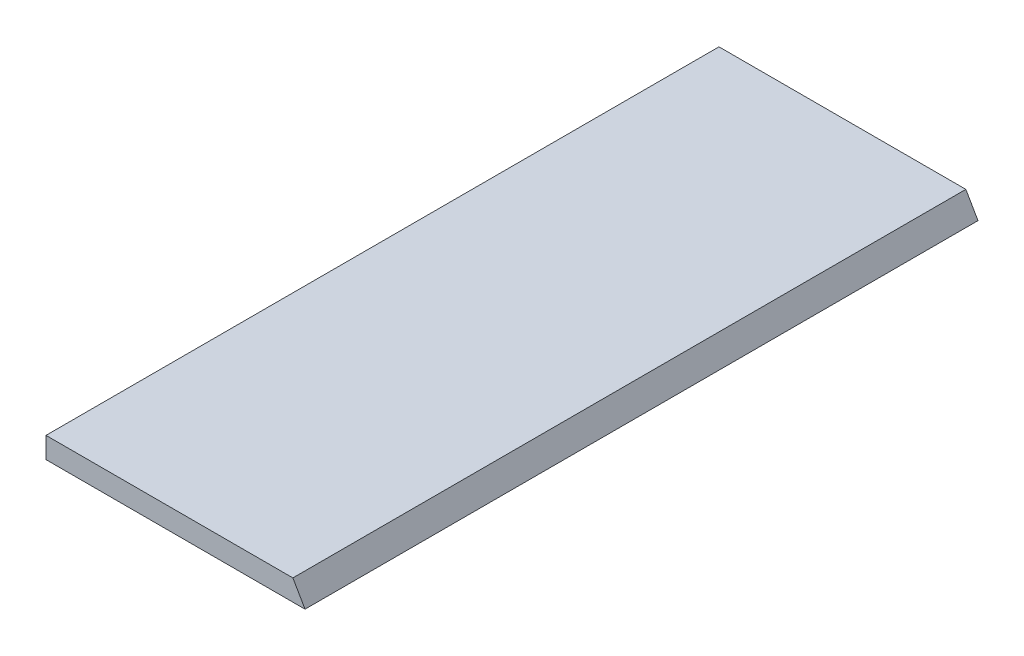
SolidWorks part; units mm, degrees
material "Oak"
ref_plane "Front Plane" through (0, 0, 0) normal (0, 0, 1) x (1, 0, 0)
ref_plane "Top Plane" through (0, 0, 0) normal (0, 1, 0) x (1, 0, 0)
ref_plane "Right Plane" through (0, 0, 0) normal (1, 0, 0) x (0, 0, -1)
sketch "Sketch1" plane through (0, 0, 0) normal (0, 1, 0) x (1, 0, 0)
  line L1 (-117.3176, -304.8) -> (117.3176, -304.8)
  line L2 (-117.3176, -304.8) -> (-117.3176, 304.8)
  line L3 (-117.3176, 304.8) -> (117.3176, 304.8)
  line L4 (117.3176, -304.8) -> (117.3176, 304.8)
  line L5 (-117.3176, -304.8) -> (117.3176, 304.8) construction
  line L6 (-117.3176, 304.8) -> (117.3176, -304.8) construction
  line L7 (234.6351, 508) -> (117.3176, 711.2) construction
  line L8 (117.3176, 711.2) -> (-117.3176, 711.2) construction
  line L9 (-117.3176, 711.2) -> (-234.6351, 508) construction
  line L10 (-234.6351, 508) -> (-117.3176, 304.8) construction
  line L11 (-117.3176, 304.8) -> (117.3176, 304.8) construction
  line L12 (117.3176, 304.8) -> (234.6351, 508) construction
  circle A0 centre (0, 508) radius 203.2 construction
  point P0 (0, 0)
  dimension "D1" = 609.6
  dimension "D2" = 406.4
extrude "Boss-Extrude1" add sketch "Sketch1" along normal blind 19.05
sketch "Sketch2" plane through (0, 0, 304.8) normal (0, 0, 1) x (1, 0, 0)
  line L0 (117.3176, 19.05) -> (117.3176, 0)
  line L1 (117.3176, 0) -> (106.3191, 19.05)
  line L2 (-117.3176, 19.05) -> (117.3176, 19.05) construction
  line L3 (106.3191, 19.05) -> (117.3176, 19.05)
  dimension "D1" = 30
extrude "Cut-Extrude1" cut sketch "Sketch2" against normal through all
